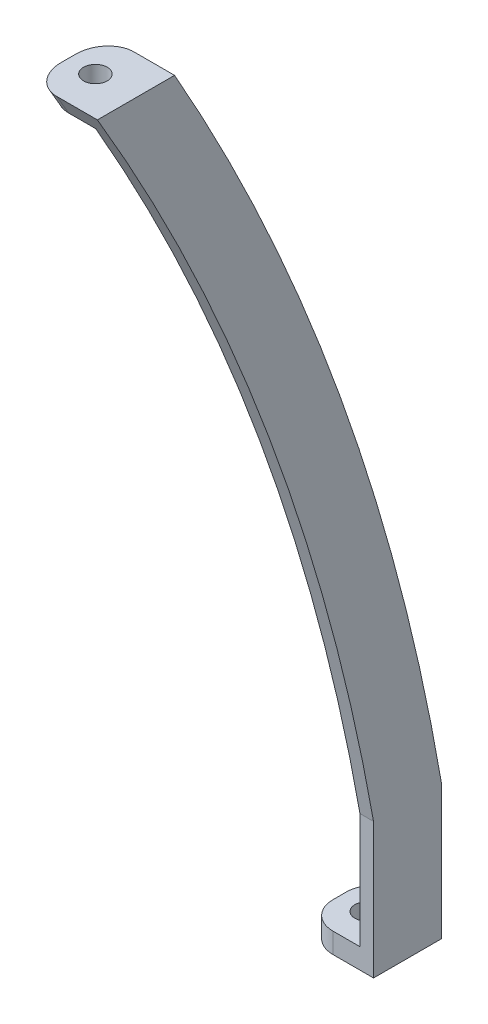
SolidWorks part; units mm, degrees
ref_plane "Front Plane" through (0, 0, 0) normal (0, 0, 1) x (1, 0, 0)
ref_plane "Top Plane" through (0, 0, 0) normal (0, 1, 0) x (1, 0, 0)
ref_plane "Right Plane" through (0, 0, 0) normal (1, 0, 0) x (0, 0, -1)
sketch "Sketch1" plane through (0, 0, 0) normal (1, 0, 0) x (0, 0, -1)
  line L0 (-40.7368, 130) -> (-29.3536, 130)
  line L1 (0, 0) -> (10, 0)
  line L2 (0, 0) -> (0, 20)
  line L4 (10, 0) -> (10, 20)
  arc A0 (0, 20) -> (-40.7368, 130) centre (-324.5568, -37.6516) ccw
  arc A1 (10, 20) -> (-29.3536, 130) centre (-324.5568, -37.6516) ccw
  dimension "D1" = 10
  dimension "D2" = 20
  dimension "D3" = 130
extrude "Boss-Extrude1" add sketch "Sketch1" along normal blind 2
sketch "Sketch2" plane through (0, 0, 0) normal (1, 0, 0) x (0, 0, -1)
  line L0 (10, 0) -> (10, 20) construction
  line L1 (0, 0) -> (10, 0)
  line L2 (0, 0) -> (0, 3)
  line L3 (0, 3) -> (10, 3)
  line L4 (10, 0) -> (10, 3)
  line L5 (-40.7368, 130) -> (-29.3536, 130)
  line L6 (-38.986, 127) -> (-27.6699, 127)
  arc A0 (0, 20) -> (-40.7368, 130) centre (-324.5568, -37.6516) ccw construction
  arc A1 (10, 20) -> (-29.3536, 130) centre (-324.5568, -37.6516) ccw construction
  arc A2 (-40.7368, 130) -> (-38.986, 127) centre (-324.5568, -37.6516) cw
  arc A3 (-29.3536, 130) -> (-27.6699, 127) centre (-324.5568, -37.6516) cw
  dimension "D1" = 3
  dimension "D2" = 3
extrude "Boss-Extrude2" add sketch "Sketch2" against normal blind 8
fillet "Fillet1" radius 4 4 edges at (-8, 1.5, -10) (-8, 1.5, 0) (-8, 128.5021, 28.508) (-8, 128.5023, 39.8575)
sketch "Sketch3" plane through (0, 3, 0) normal (0, 1, 0) x (1, 0, 0)
  line L0 (-8, 5) -> (-4, 5) construction
  line L1 (-8, 6) -> (-8, 4) construction
  line L2 (-8, -35.0317) -> (-4, -35.0317) construction
  line L3 (-8, -33.9626) -> (-8, -36.1008) construction
  circle A0 centre (-4, 5) radius 1.75
  circle A1 centre (-4, -35.0317) radius 1.75
  dimension "D2" = 3.5
  dimension "D4" = 3.5
  dimension "D1" = 4
  dimension "D3" = 4
extrude "Cut-Extrude1" cut sketch "Sketch3" against normal through all both and the other way through all
